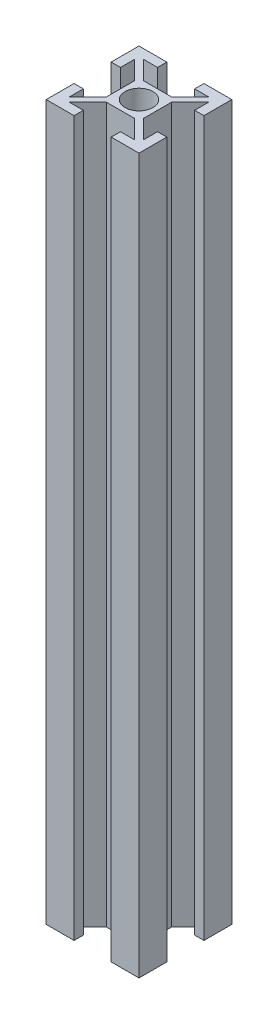
SolidWorks part; units mm, degrees
material "1060 Alloy"
ref_plane "Front Plane" through (0, 0, 0) normal (0, 0, 1) x (1, 0, 0)
ref_plane "Top Plane" through (0, 0, 0) normal (0, 1, 0) x (1, 0, 0)
ref_plane "Right Plane" through (0, 0, 0) normal (1, 0, 0) x (0, 0, -1)
sketch "2020 sketch" plane through (0, 0, 0) normal (0, 1, 0) x (1, 0, 0)
  line L0 (-4, 10) -> (-4, 8)
  line L1 (-10, 10) -> (-4, 10)
  line L2 (-10, 10) -> (-10, 4)
  line L3 (-10, -10) -> (-4, -10)
  line L4 (10, 10) -> (10, 4)
  line L5 (-10, 10) -> (10, -10) construction
  line L6 (-10, -10) -> (10, 10) construction
  line L7 (-4, 8) -> (-7, 8)
  line L8 (-7, 8) -> (-3, 4)
  line L9 (-3, 4) -> (3, 4)
  line L10 (3, 4) -> (7, 8)
  line L11 (7, 8) -> (4, 8)
  line L12 (4, 8) -> (4, 10)
  line L13 (4, 3) -> (4, -3)
  line L14 (8, 7) -> (4, 3)
  line L15 (8, 4) -> (8, 7)
  line L16 (10, 4) -> (8, 4)
  line L17 (8, -4) -> (10, -4)
  line L18 (8, -7) -> (8, -4)
  line L19 (4, -3) -> (8, -7)
  line L20 (3, -4) -> (-3, -4)
  line L21 (7, -8) -> (3, -4)
  line L22 (4, -8) -> (7, -8)
  line L23 (4, -10) -> (4, -8)
  line L24 (-4, -8) -> (-4, -10)
  line L25 (-7, -8) -> (-4, -8)
  line L26 (-3, -4) -> (-7, -8)
  line L27 (-4, -3) -> (-4, 3)
  line L28 (-8, -7) -> (-4, -3)
  line L29 (-8, -4) -> (-8, -7)
  line L30 (-10, -4) -> (-8, -4)
  line L31 (-8, 4) -> (-10, 4)
  line L32 (-8, 7) -> (-8, 4)
  line L33 (-4, 3) -> (-8, 7)
  line L34 (-10, -4) -> (-10, -10)
  line L35 (10, -4) -> (10, -10)
  line L36 (4, 10) -> (10, 10)
  line L37 (4, -10) -> (10, -10)
  circle A0 centre (0, 0) radius 3
  point P0 (0, 0)
  point P14 (4, 9)
  point P42 (0, 0)
  dimension "D9" = 6
  dimension "D1" = 20
  dimension "D2" = 20
  dimension "D3" = 8
  dimension "D4" = 6
  dimension "D5" = 6
  dimension "D6" = 2
  dimension "D7" = 4
  dimension "D8" = 4
extrude "Boss-Extrude1" add sketch "2020 sketch" along normal blind 154 contours A0 | L28 L27 L33 L32 L31 L2 L1 L0 L7 L8 L9 L10 L11 L12 L36 L4 L16 L15 L14 L13 L19 L18 L17 L35 L37 L23 L22 L21 L20 L26 L25 L24 L3 L34 L30 L29
